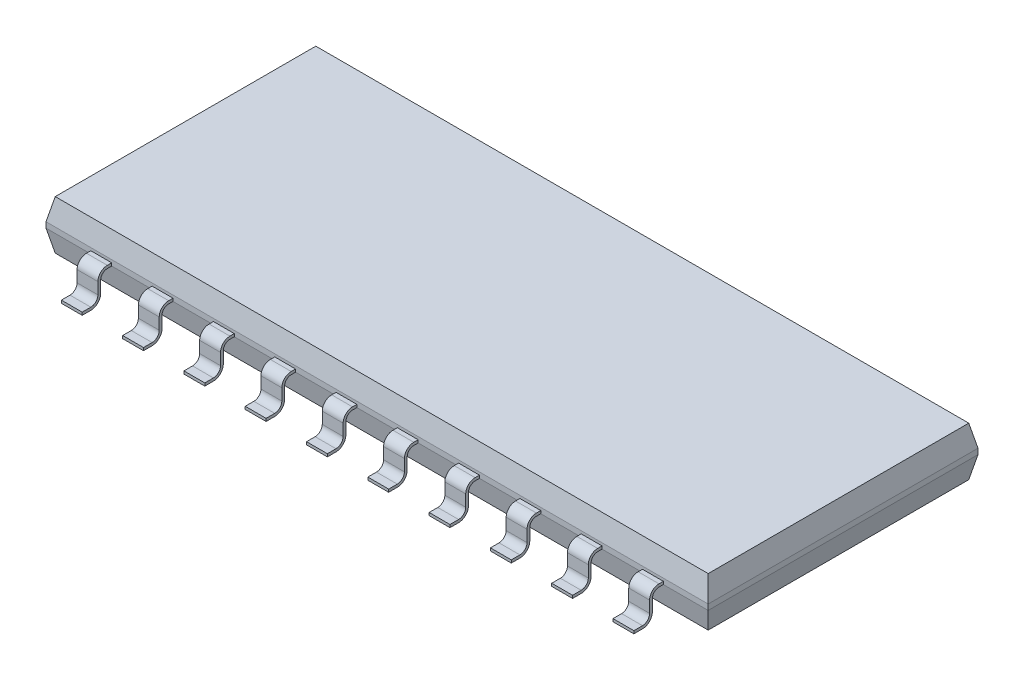
SolidWorks part; units mm, degrees
ref_plane "Front Plane" through (0, 0, 0) normal (0, 0, 1) x (1, 0, 0)
ref_plane "Top Plane" through (0, 0, 0) normal (0, 1, 0) x (1, 0, 0)
ref_plane "Right Plane" through (0, 0, 0) normal (1, 0, 0) x (0, 0, -1)
sketch "Sketch1" plane through (0, 0, 0) normal (0, 1, 0) x (1, 0, 0)
  line L1 (-6.86, -2.795) -> (6.86, -2.795)
  line L2 (-6.86, -2.795) -> (-6.86, 2.795)
  line L3 (-6.86, 2.795) -> (6.86, 2.795)
  line L4 (6.86, -2.795) -> (6.86, 2.795)
  line L5 (-6.86, -2.795) -> (6.86, 2.795) construction
  line L6 (-6.86, 2.795) -> (6.86, -2.795) construction
  point P0 (0, 0)
  dimension "D1" = 5.59
  dimension "D2" = 13.72
extrude "Boss-Extrude1" add sketch "Sketch1" along normal mid plane 1.015
chamfer "Chamfer1" distance 0.45 angle 12 4 edges at (-6.86, 0.5075, 0) (0, 0.5075, -2.795) (0, 0.5075, 2.795) (6.86, 0.5075, 0)
chamfer "Chamfer3" distance 0.45 angle 12 4 edges at (0, -0.5075, -2.795) (-6.86, -0.5075, 0) (0, -0.5075, 2.795) (6.86, -0.5075, 0)
ref_plane "Plane1" through (0, -0.6375, 0) normal (0, -1, 0) x (-1, 0, 0)
sketch "Sketch4" plane through (0, -0.6375, 0) normal (0, -1, 0) x (-1, 0, 0)
  line L0 (0, 1.4884) -> (0, -3.7692) construction
  line L1 (-5.715, -2.795) -> (-5.715, -3.406) construction
  line L2 (-6.86, -2.795) -> (6.86, -2.795) construction
  line L3 (-4.661, -2.795) -> (-4.661, -3.406)
  line L4 (-5.499, -2.795) -> (-5.931, -2.795)
  line L5 (-5.499, -2.795) -> (-5.499, -3.406)
  line L6 (-5.499, -3.406) -> (-5.931, -3.406)
  line L7 (-5.931, -2.795) -> (-5.931, -3.406)
  line L8 (-4.229, -3.406) -> (-4.661, -3.406)
  line L9 (-4.229, -2.795) -> (-4.229, -3.406)
  line L10 (-4.229, -2.795) -> (-4.661, -2.795)
  line L11 (-3.391, -2.795) -> (-3.391, -3.406)
  line L12 (-2.959, -3.406) -> (-3.391, -3.406)
  line L13 (-2.959, -2.795) -> (-2.959, -3.406)
  line L14 (-2.959, -2.795) -> (-3.391, -2.795)
  line L15 (-2.121, -2.795) -> (-2.121, -3.406)
  line L16 (-1.689, -3.406) -> (-2.121, -3.406)
  line L17 (-1.689, -2.795) -> (-1.689, -3.406)
  line L18 (-1.689, -2.795) -> (-2.121, -2.795)
  line L19 (-0.851, -2.795) -> (-0.851, -3.406)
  line L20 (-0.419, -3.406) -> (-0.851, -3.406)
  line L21 (-0.419, -2.795) -> (-0.419, -3.406)
  line L22 (-0.419, -2.795) -> (-0.851, -2.795)
  line L23 (0.419, -2.795) -> (0.419, -3.406)
  line L24 (0.851, -3.406) -> (0.419, -3.406)
  line L25 (0.851, -2.795) -> (0.851, -3.406)
  line L26 (0.851, -2.795) -> (0.419, -2.795)
  line L27 (1.689, -2.795) -> (1.689, -3.406)
  line L28 (2.121, -3.406) -> (1.689, -3.406)
  line L29 (2.121, -2.795) -> (2.121, -3.406)
  line L30 (2.121, -2.795) -> (1.689, -2.795)
  line L31 (2.959, -2.795) -> (2.959, -3.406)
  line L32 (3.391, -3.406) -> (2.959, -3.406)
  line L33 (3.391, -2.795) -> (3.391, -3.406)
  line L34 (3.391, -2.795) -> (2.959, -2.795)
  line L35 (4.229, -2.795) -> (4.229, -3.406)
  line L36 (4.661, -3.406) -> (4.229, -3.406)
  line L37 (4.661, -2.795) -> (4.661, -3.406)
  line L38 (4.661, -2.795) -> (4.229, -2.795)
  line L39 (5.499, -2.795) -> (5.499, -3.406)
  line L40 (5.931, -3.406) -> (5.499, -3.406)
  line L41 (5.931, -2.795) -> (5.931, -3.406)
  line L42 (5.931, -2.795) -> (5.499, -2.795)
  point P12 (-5.499, -3.1005)
  dimension "D1" = 5.715
  dimension "D2" = 0.611
  dimension "D3" = 0.432
  dimension "D4" = 10
extrude "Boss-Extrude2" add sketch "Sketch4" along normal up to surface (0.6375 mm away) from surface at -0.6375 separate body contours L5 L4 L7 L6 | L3 L8 L9 L10 | L11 L12 L13 L14 | L15 L16 L17 L18 | L19 L20 L21 L22 | L23 L24 L25 L26 | L27 L28 L29 L30 | L31 L32 L33 L34 | L35 L36 L37 L38 | L39 L40 L41 L42 up to plane "Plane1" starting at plane "Top Plane"
sketch "Sketch5" plane through (5.931, 0, 0) normal (1, 0, 0) x (0, 0, -1)
  line L0 (-2.795, -0.0575) -> (-2.8852, -0.0575)
  line L1 (-3.0226, -0.1949) -> (-3.0226, -0.4328)
  line L2 (-2.795, -0.6375) -> (-3.406, -0.6375) construction
  line L3 (-3.2273, -0.6375) -> (-2.795, -0.6375)
  line L4 (-2.9693, -0.6375) -> (2.9693, -0.6375) construction
  line L5 (-2.795, -0.6375) -> (-2.795, -0.0575)
  line L6 (-3.406, -0.58) -> (-3.2273, -0.58)
  line L7 (-3.406, -0.6375) -> (-3.406, 0) construction
  line L8 (-3.0801, -0.4328) -> (-3.0801, -0.1949)
  line L9 (-2.795, 0) -> (-3.406, 0) construction
  line L10 (-2.8852, 0) -> (-3.406, 0)
  line L11 (-3.406, 0) -> (-3.406, -0.58)
  arc A0 (-2.8852, -0.0575) -> (-3.0226, -0.1949) centre (-2.8852, -0.1949) ccw
  arc A1 (-3.0226, -0.4328) -> (-3.2273, -0.6375) centre (-3.2273, -0.4328) cw
  arc A2 (-3.2273, -0.58) -> (-3.0801, -0.4328) centre (-3.2273, -0.4328) ccw
  arc A3 (-3.0801, -0.1949) -> (-2.8852, 0) centre (-2.8852, -0.1949) cw
  point P3 (-2.9023, -0.0575)
  point P10 (0, 0)
  point P24 (-3.2524, -0.1949)
  point P27 (-3.4571, -0.5075)
  point P28 (0, 0)
  point P29 (0, 0)
  line M3 (-3.406, -0.6375) -> (-2.795, -0.6375)
  line M4 (-2.795, -0.6375) -> (-2.795, 0)
extrude "Cut-Extrude1" cut sketch "Sketch5" against normal through all contours L1 A1 L0 A0 M3 M4 | L11 L6 A2 L8 A3 L10
mirror "Mirror1" about plane through (0, 0, 0) normal (0, 0, 1) of "Boss-Extrude2", "Cut-Extrude1"
